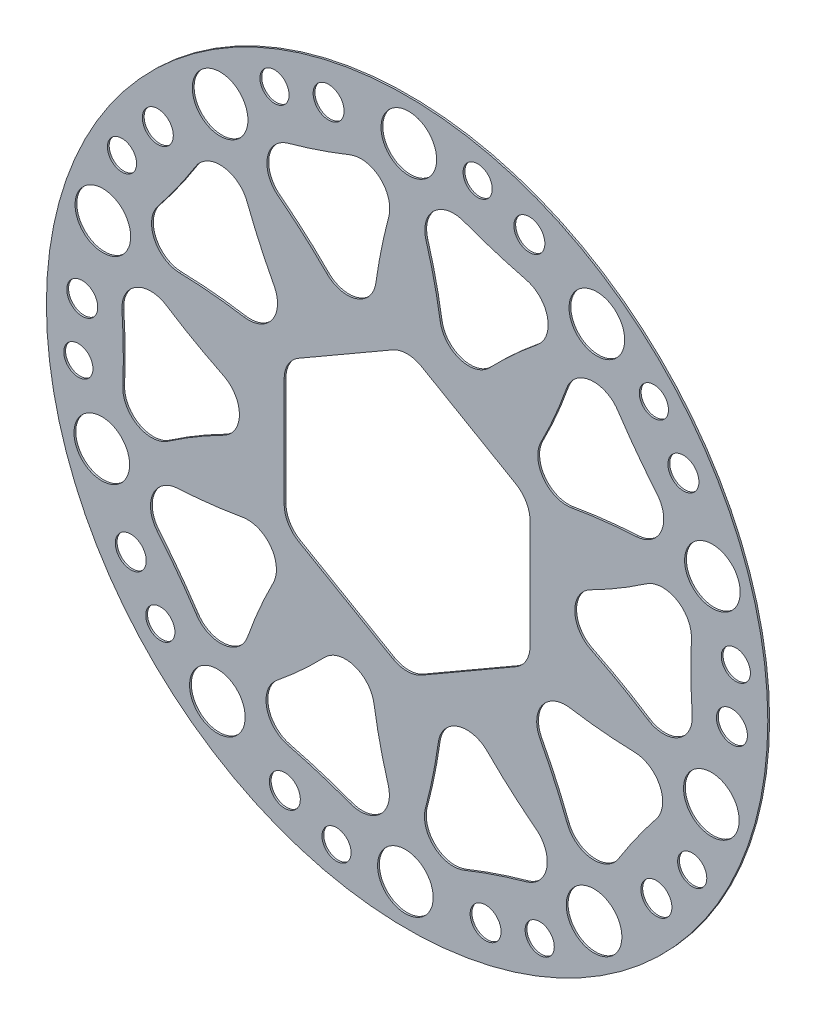
SolidWorks part; units mm, degrees
ref_plane "Front Plane" through (0, 0, 0) normal (0, 0, 1) x (1, 0, 0)
ref_plane "Top Plane" through (0, 0, 0) normal (0, 1, 0) x (1, 0, 0)
ref_plane "Right Plane" through (0, 0, 0) normal (1, 0, 0) x (0, 0, -1)
sketch "Sketch4" plane through (0, 0, 0) normal (0, 0, 1) x (1, 0, 0)
  line L1 (-30.0832, -21.9873) -> (-4, -37.0465)
  line L2 (4, -37.0465) -> (30.0832, -21.9873)
  line L3 (34.0832, -15.0591) -> (34.0832, 15.0591)
  line L4 (30.0832, 21.9873) -> (4, 37.0465)
  line L5 (-4, 37.0465) -> (-30.0832, 21.9873)
  line L6 (-34.0832, 15.0591) -> (-34.0832, -15.0591)
  circle A0 centre (0, 0) radius 34.0832 construction
  arc A1 (-4, 37.0465) -> (4, 37.0465) centre (0, 30.1183) cw
  arc A2 (34.0832, 15.0591) -> (30.0832, 21.9873) centre (26.0832, 15.0591) ccw
  arc A3 (-34.0832, 15.0591) -> (-30.0832, 21.9873) centre (-26.0832, 15.0591) cw
  arc A4 (-30.0832, -21.9873) -> (-34.0832, -15.0591) centre (-26.0832, -15.0591) cw
  arc A5 (4, -37.0465) -> (-4, -37.0465) centre (0, -30.1183) cw
  arc A6 (30.0832, -21.9873) -> (34.0832, -15.0591) centre (26.0832, -15.0591) ccw
  circle A7 centre (0, 0) radius 100
  arc A8 (-79.0414, 9.0757) -> (-78.8195, -9.0882) centre (-240.5157, -1.9807) cw
  arc A9 (-50.9788, 7.4539) -> (-66.712, 16.3374) centre (14.3421, 141.5154) cw
  arc A10 (-50.8677, -6.8743) -> (-66.2937, -16.031) centre (9.8734, -126.7755) ccw
  arc A11 (-79.0414, 9.0757) -> (-66.712, 16.3374) centre (-71.0601, 9.6222) cw
  arc A12 (-66.2937, -16.031) -> (-78.8195, -9.0882) centre (-70.8272, -9.4395) cw
  arc A13 (-50.8677, -6.8743) -> (-50.9788, 7.4539) centre (-54.483, 0.2622) ccw
  arc A14 (-58.6113, 53.8018) -> (-69.1082, 38.9764) centre (-195.7455, 139.7691) cw
  arc A15 (-36.8614, 35.995) -> (-44.3682, 52.4295) centre (94.7837, 106.0583) cw
  arc A16 (-45.1934, 24.3378) -> (-63.0555, 25.9971) centre (-66.529, -108.367) ccw
  arc A17 (-58.6113, 53.8018) -> (-44.3682, 52.4295) centre (-51.833, 49.5526) cw
  arc A18 (-63.0555, 25.9971) -> (-69.1082, 38.9764) centre (-62.8488, 33.9945) cw
  arc A19 (-45.1934, 24.3378) -> (-36.8614, 35.995) centre (-43.9235, 32.2364) ccw
  arc A20 (-15.7936, 77.9774) -> (-32.9999, 72.1534) centre (-76.2072, 228.1319) cw
  arc A21 (-8.6642, 50.7871) -> (-5.0774, 68.4954) centre (139.0211, 30.0905) cw
  arc A22 (-22.2568, 46.2538) -> (-35.7323, 58.0952) centre (-117.5196, -48.5659) ccw
  arc A23 (-15.7936, 77.9774) -> (-5.0774, 68.4954) centre (-12.8075, 70.5556) cw
  arc A24 (-35.7323, 58.0952) -> (-32.9999, 72.1534) centre (-30.8643, 64.4437) cw
  arc A25 (-22.2568, 46.2538) -> (-8.6642, 50.7871) centre (-16.5868, 51.8974) ccw
  arc A26 (33.0566, 72.3683) -> (15.7132, 77.7702) centre (72.4396, 229.3561) cw
  arc A27 (22.8424, 46.1803) -> (36.1529, 58.3983) centre (130.1572, -57.3708) cw
  arc A28 (9.1811, 50.5023) -> (5.2395, 68.0029) centre (-123.6217, 29.7856) ccw
  arc A29 (33.0566, 72.3683) -> (36.1529, 58.3983) centre (31.11, 64.6088) cw
  arc A30 (5.2395, 68.0029) -> (15.7132, 77.7702) centre (12.9093, 70.2776) cw
  arc A31 (9.1811, 50.5023) -> (22.8424, 46.1803) centre (17.0855, 51.7354) ccw
  arc A32 (69.2804, 39.117) -> (58.4244, 53.6814) centre (193.417, 142.974) cw
  arc A33 (45.624, 23.9342) -> (63.574, 25.9951) centre (71.5776, -122.9185) cw
  arc A34 (37.1122, 35.4607) -> (44.21, 51.9358) centre (-82.5045, 96.7601) ccw
  arc A35 (69.2804, 39.117) -> (63.574, 25.9951) centre (63.1446, 33.9836) cw
  arc A36 (44.21, 51.9358) -> (58.4244, 53.6814) centre (51.752, 49.2679) cw
  arc A37 (37.1122, 35.4607) -> (45.624, 23.9342) centre (44.2318, 31.8122) ccw
  arc A38 (79.0414, -9.0757) -> (78.8195, 9.0882) centre (240.5157, 1.9807) cw
  arc A39 (50.9788, -7.4539) -> (66.712, -16.3374) centre (-14.3421, -141.5154) cw
  arc A40 (50.8677, 6.8743) -> (66.2937, 16.031) centre (-9.8734, 126.7755) ccw
  arc A41 (79.0414, -9.0757) -> (66.712, -16.3374) centre (71.0601, -9.6222) cw
  arc A42 (66.2937, 16.031) -> (78.8195, 9.0882) centre (70.8272, 9.4395) cw
  arc A43 (50.8677, 6.8743) -> (50.9788, -7.4539) centre (54.483, -0.2622) ccw
  arc A44 (58.6113, -53.8018) -> (69.1082, -38.9764) centre (195.7455, -139.7691) cw
  arc A45 (36.8614, -35.995) -> (44.3682, -52.4295) centre (-94.7837, -106.0583) cw
  arc A46 (45.1934, -24.3378) -> (63.0555, -25.9971) centre (66.529, 108.367) ccw
  arc A47 (58.6113, -53.8018) -> (44.3682, -52.4295) centre (51.833, -49.5526) cw
  arc A48 (63.0555, -25.9971) -> (69.1082, -38.9764) centre (62.8488, -33.9945) cw
  arc A49 (45.1934, -24.3378) -> (36.8614, -35.995) centre (43.9235, -32.2364) ccw
  arc A50 (15.7936, -77.9774) -> (32.9999, -72.1534) centre (76.2072, -228.1319) cw
  arc A51 (8.6642, -50.7871) -> (5.0774, -68.4954) centre (-139.0211, -30.0905) cw
  arc A52 (22.2568, -46.2538) -> (35.7323, -58.0952) centre (117.5196, 48.5659) ccw
  arc A53 (15.7936, -77.9774) -> (5.0774, -68.4954) centre (12.8075, -70.5556) cw
  arc A54 (35.7323, -58.0952) -> (32.9999, -72.1534) centre (30.8643, -64.4437) cw
  arc A55 (22.2568, -46.2538) -> (8.6642, -50.7871) centre (16.5868, -51.8974) ccw
  arc A56 (-33.0566, -72.3683) -> (-15.7132, -77.7702) centre (-72.4396, -229.3561) cw
  arc A57 (-22.8424, -46.1803) -> (-36.1529, -58.3983) centre (-130.1572, 57.3708) cw
  arc A58 (-9.1811, -50.5023) -> (-5.2395, -68.0029) centre (123.6217, -29.7856) ccw
  arc A59 (-33.0566, -72.3683) -> (-36.1529, -58.3983) centre (-31.11, -64.6088) cw
  arc A60 (-5.2395, -68.0029) -> (-15.7132, -77.7702) centre (-12.9093, -70.2776) cw
  arc A61 (-9.1811, -50.5023) -> (-22.8424, -46.1803) centre (-17.0855, -51.7354) ccw
  arc A62 (-69.2804, -39.117) -> (-58.4244, -53.6814) centre (-193.417, -142.974) cw
  arc A63 (-45.624, -23.9342) -> (-63.574, -25.9951) centre (-71.5776, 122.9185) cw
  arc A64 (-37.1122, -35.4607) -> (-44.21, -51.9358) centre (82.5045, -96.7601) ccw
  arc A65 (-69.2804, -39.117) -> (-63.574, -25.9951) centre (-63.1446, -33.9836) cw
  arc A66 (-44.21, -51.9358) -> (-58.4244, -53.6814) centre (-51.752, -49.2679) cw
  arc A67 (-37.1122, -35.4607) -> (-45.624, -23.9342) centre (-44.2318, -31.8122) ccw
  circle A68 centre (-51.833, 72.1534) radius 7.7097
  circle A69 centre (0.4769, 88.84) radius 7.7097
  circle A70 centre (52.6046, 71.5928) radius 7.7097
  circle A71 centre (84.6392, 26.9995) radius 7.7097
  circle A72 centre (84.3445, -27.9066) radius 7.7097
  circle A73 centre (51.833, -72.1534) radius 7.7097
  circle A74 centre (-0.4769, -88.84) radius 7.7097
  circle A75 centre (-52.6046, -71.5928) radius 7.7097
  circle A76 centre (-84.6392, -26.9995) radius 7.7097
  circle A77 centre (-84.3445, 27.9066) radius 7.7097
  circle A78 centre (-69.1082, 58.0952) radius 4.2935
  circle A79 centre (-79.0414, 46.2538) radius 4.0433
  circle A80 centre (-36.7586, 83.8795) radius 4.0433
  circle A81 centre (-21.7622, 87.6208) radius 4.2935
  circle A82 centre (19.5648, 89.4661) radius 4.0433
  circle A83 centre (33.8962, 83.6782) radius 4.2935
  circle A84 centre (68.4151, 60.8797) radius 4.0433
  circle A85 centre (76.6075, 47.7734) radius 4.2935
  circle A86 centre (91.1331, 9.0393) radius 4.0433
  circle A87 centre (90.0572, -6.3793) radius 4.2935
  circle A88 centre (79.0414, -46.2538) radius 4.0433
  circle A89 centre (69.1082, -58.0952) radius 4.2935
  circle A90 centre (36.7586, -83.8795) radius 4.0433
  circle A91 centre (21.7622, -87.6208) radius 4.2935
  circle A92 centre (-19.5648, -89.4661) radius 4.0433
  circle A93 centre (-33.8962, -83.6782) radius 4.2935
  circle A94 centre (-68.4151, -60.8797) radius 4.0433
  circle A95 centre (-76.6075, -47.7734) radius 4.2935
  circle A96 centre (-91.1331, -9.0393) radius 4.0433
  circle A97 centre (-90.0572, 6.3793) radius 4.2935
  point P1 (63.6479, 46.2468)
  point P12 (0, 39.3559)
  point P15 (34.0832, 19.6779)
  point P18 (-34.0832, 19.6779)
  point P23 (0, -39.3559)
  point P149 (0, 0)
  point P172 (0, 0)
  point P213 (0, 0)
  dimension "D1" = 8
  dimension "D2" = 8
  dimension "D3" = 200
  dimension "D7" = 167.7589
  dimension "D8" = 78.6754
  dimension "D4" = 10
  dimension "D5" = 10
  dimension "D6" = 10
extrude "Boss-Extrude3" add sketch "Sketch4" along normal blind 0.5
